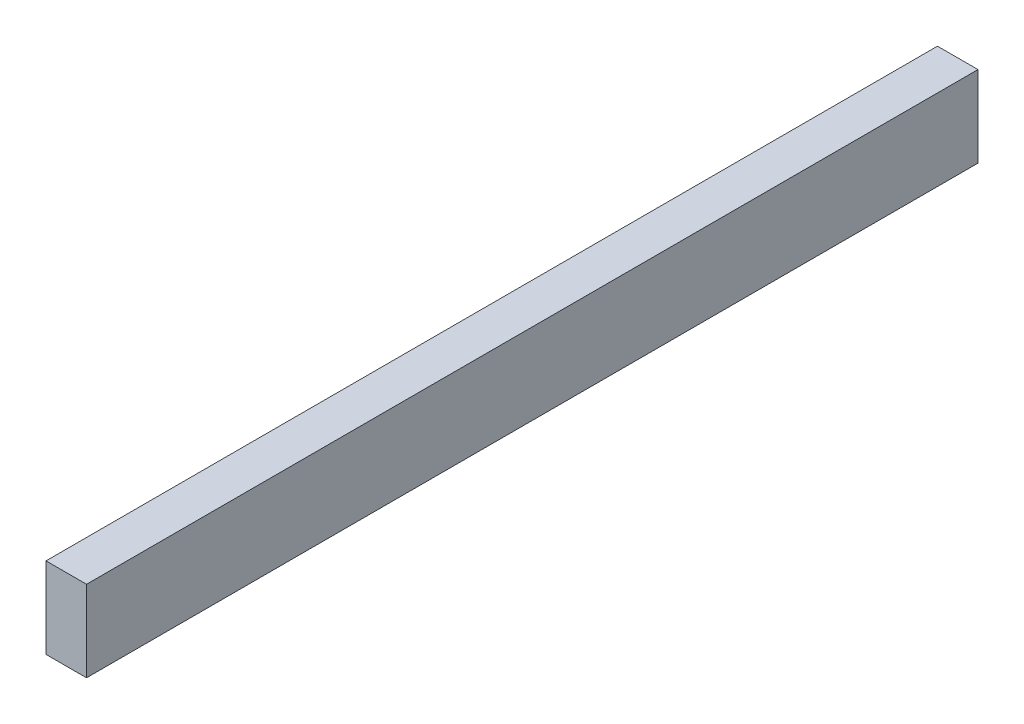
SolidWorks part; units mm, degrees
material "Brass"
ref_plane "Front Plane" through (0, 0, 0) normal (0, 0, 1) x (1, 0, 0)
ref_plane "Top Plane" through (0, 0, 0) normal (0, 1, 0) x (1, 0, 0)
ref_plane "Right Plane" through (0, 0, 0) normal (1, 0, 0) x (0, 0, -1)
sketch "Sketch1" plane through (0, 0, 0) normal (0, 0, 1) x (1, 0, 0)
  line L1 (1.5875, -3.175) -> (-1.5875, -3.175)
  line L2 (1.5875, -3.175) -> (1.5875, 3.175)
  line L3 (1.5875, 3.175) -> (-1.5875, 3.175)
  line L4 (-1.5875, -3.175) -> (-1.5875, 3.175)
  line L5 (1.5875, -3.175) -> (-1.5875, 3.175) construction
  line L6 (1.5875, 3.175) -> (-1.5875, -3.175) construction
  point P0 (0, 0)
  dimension "D1" = 3.175
  dimension "D2" = 6.35
extrude "Boss-Extrude1" add sketch "Sketch1" along normal blind 69.85
